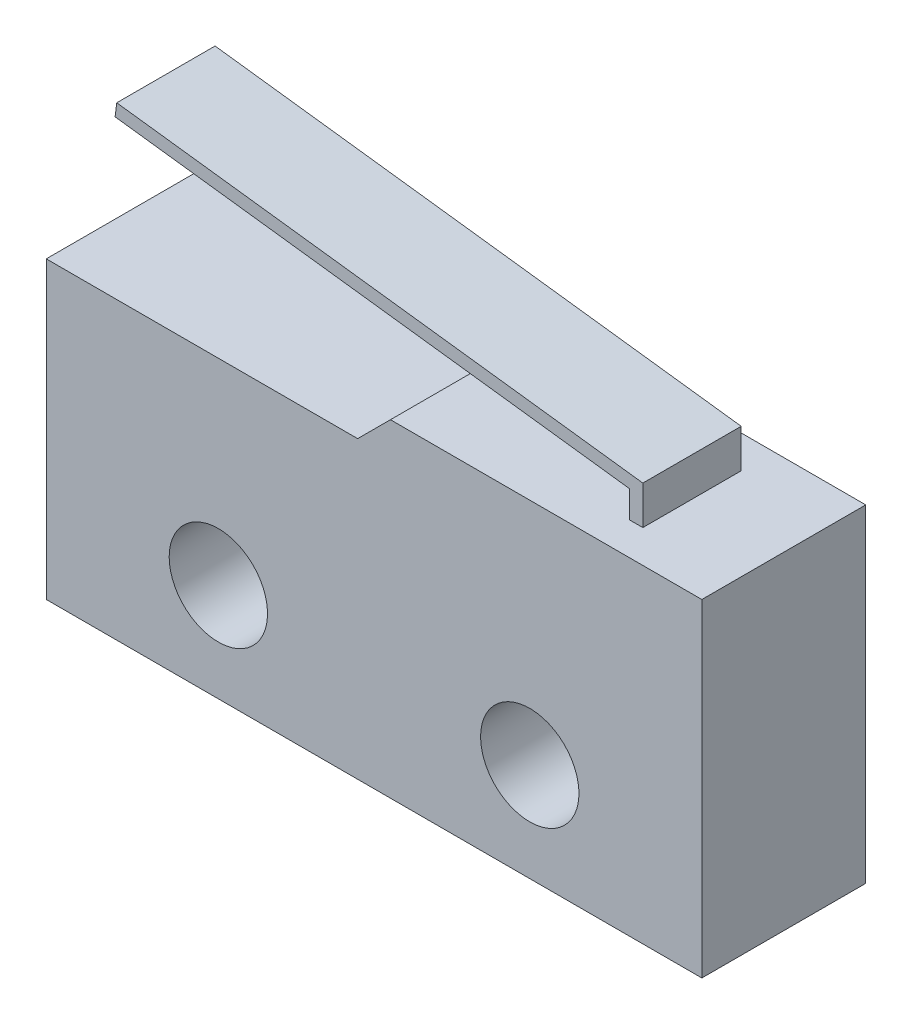
SolidWorks part; units mm, degrees
ref_plane "Front Plane" through (0, 0, 0) normal (0, 0, 1) x (1, 0, 0)
ref_plane "Top Plane" through (0, 0, 0) normal (0, 1, 0) x (1, 0, 0)
ref_plane "Right Plane" through (0, 0, 0) normal (1, 0, 0) x (0, 0, -1)
sketch "Sketch1" plane through (0, 0, 0) normal (0, 0, 1) x (1, 0, 0)
  line L0 (-10, 4) -> (-0.5, 4)
  line L1 (-10, -5) -> (10, -5)
  line L2 (-10, -5) -> (-10, 4)
  line L3 (0.5, 5) -> (10, 5)
  line L4 (10, -5) -> (10, 5)
  line L5 (-10, -5) -> (10, 5) construction
  line L6 (-10, 5) -> (10, -5) construction
  line L7 (-0.5, 4) -> (0.5, 5)
  point P0 (0, 0)
  point P8 (0, 4.5)
  dimension "D1" = 10
  dimension "D2" = 20
  dimension "D3" = 1
  dimension "D4" = 1
extrude "Boss-Extrude1" add sketch "Sketch1" along normal mid plane 5
hole_wizard "Ø3.0 (3) Diameter Hole1" positions "Sketch3" profile "Sketch4" hole size "Ø3.0" standard "Ansi Metric"
sketch "Sketch3" plane through (0, 0, -2.5) normal (0, 0, -1) x (-1, 0, 0)
  line L0 (10, -5) -> (-10, -5) construction
  line L1 (-10, -5) -> (-10, 5) construction
  point P0 (-4.75, -2)
  point P1 (4.75, -2)
  dimension "D1" = 9.5
  dimension "D2" = 3
  dimension "D3" = 5.25
sketch "Sketch4" plane through (4.75, -2, -2.5) normal (1, 0, 0) x (0, 1, 0)
  line L0 (0, 0) -> (0, 5.9013)
  line L1 (0, 5.9013) -> (1.5, 5)
  line L2 (1.5, 5) -> (1.5, 0)
  line L5 (1.5, 0) -> (0, 0)
  line L10 (0, 5.9013) -> (-1.5, 5) construction
  line L11 (0, -6.35) -> (0, 107.95) construction
  dimension "Hole Dia." = 3
  dimension "Hole Depth" = 5
  dimension "Drill Angle" = 118
sketch "Sketch5" plane through (0, 0, 0) normal (0, 0, 1) x (1, 0, 0)
  line L0 (7, 5) -> (7, 6) construction
  line L1 (7, 6) -> (-8.8745, 8) construction
  line L2 (7.2, 5) -> (7.2, 6.1764)
  line L3 (7.2, 6.1764) -> (-8.8495, 8.1984)
  line L4 (6.8, 5) -> (6.8, 5.8236)
  line L5 (6.8, 5.8236) -> (-8.8995, 7.8016)
  line L6 (-8.8495, 8.1984) -> (-8.8995, 7.8016)
  line L7 (6.8, 5) -> (7.2, 5)
  line L8 (10, 5) -> (0.5, 5) construction
  dimension "D1" = 16
  dimension "D2" = 1
  dimension "D5" = 3
  dimension "D6" = 2
  dimension "D3" = 0.2
  dimension "D4" = 0.2
extrude "Boss-Extrude2" add sketch "Sketch5" along normal mid plane 3
